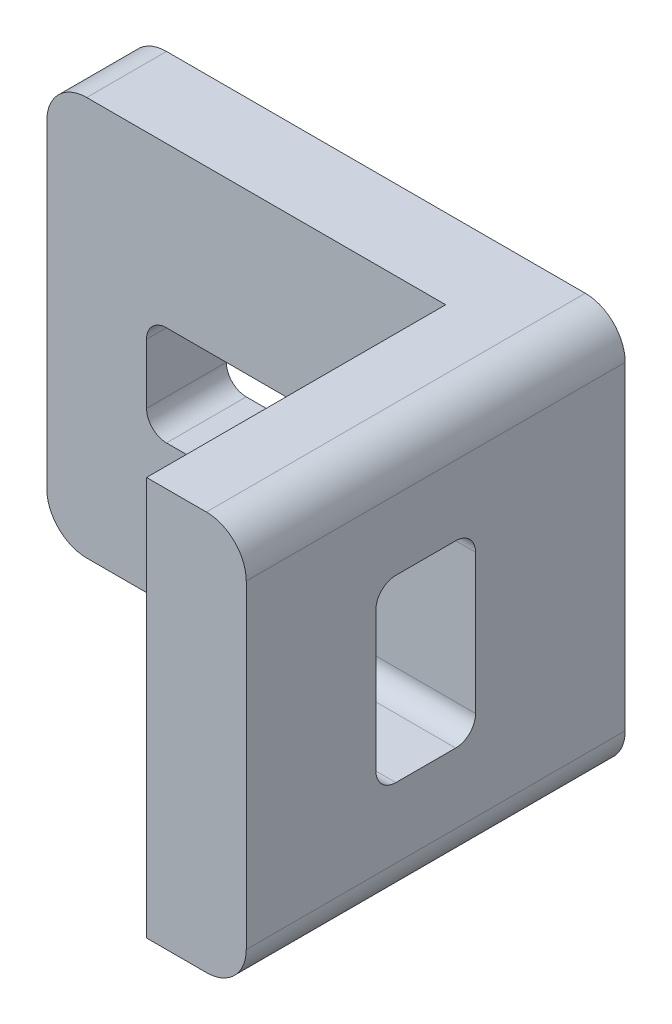
SolidWorks part; units mm, degrees
ref_plane "Plan de face" through (0, 0, 0) normal (0, 0, 1) x (1, 0, 0)
ref_plane "Plan de dessus" through (0, 0, 0) normal (0, 1, 0) x (1, 0, 0)
ref_plane "Plan de droite" through (0, 0, 0) normal (1, 0, 0) x (0, 0, -1)
sketch "Esquisse1" plane through (0, 0, 0) normal (0, 0, 1) x (1, 0, 0)
  line L1 (-11.2733, 8.7087) -> (9.7267, 8.7087)
  line L2 (-13.2733, 6.7087) -> (-13.2733, -9.2913)
  line L3 (-11.2733, -11.2913) -> (9.7267, -11.2913)
  line L4 (11.7267, 6.7087) -> (11.7267, -9.2913)
  arc A0 (9.7267, 8.7087) -> (11.7267, 6.7087) centre (9.7267, 6.7087) cw
  arc A1 (11.7267, -9.2913) -> (9.7267, -11.2913) centre (9.7267, -9.2913) cw
  arc A2 (-11.2733, -11.2913) -> (-13.2733, -9.2913) centre (-11.2733, -9.2913) cw
  arc A3 (-13.2733, 6.7087) -> (-11.2733, 8.7087) centre (-11.2733, 6.7087) cw
  point P8 (11.7267, -11.2913)
  point P11 (-13.2733, -11.2913)
  point P14 (-13.2733, 8.7087)
  dimension "D3" = 2
  dimension "D1" = 20
  dimension "D2" = 25
extrude "Boss.-Extru.1" add sketch "Esquisse1" along normal blind 4
sketch "Esquisse2" plane through (0, 0, 4) normal (0, 0, 1) x (1, 0, 0)
  line L1 (6.7267, 8.7087) -> (9.7267, 8.7087)
  line L2 (6.7267, 8.7087) -> (6.7267, -11.2913)
  line L3 (6.7267, -11.2913) -> (9.7267, -11.2913)
  line L4 (11.7267, 6.7087) -> (11.7267, -9.2913)
  line L5 (11.7267, -9.2913) -> (11.7267, 6.7087) construction
  line L6 (9.7267, 8.7087) -> (-11.2733, 8.7087) construction
  line L7 (-11.2733, -11.2913) -> (9.7267, -11.2913) construction
  arc A0 (9.7267, 8.7087) -> (11.7267, 6.7087) centre (9.7267, 6.7087) cw
  arc A1 (11.7267, -9.2913) -> (9.7267, -11.2913) centre (9.7267, -9.2913) cw
  dimension "D1" = 2
  dimension "D2" = 3
extrude "Boss.-Extru.3" add sketch "Esquisse2" along normal blind 15
sketch "Esquisse3" plane through (0, 0, 4) normal (0, 0, 1) x (1, 0, 0)
  line L0 (-13.2733, 6.7087) -> (-13.2733, -9.2913) construction
  line L1 (-7.2733, 0.7087) -> (-0.2733, 0.7087)
  line L2 (-8.2733, -0.2913) -> (-8.2733, -3.2913)
  line L3 (-7.2733, -4.2913) -> (-0.2733, -4.2913)
  line L4 (0.7267, -0.2913) -> (0.7267, -3.2913)
  line L5 (-8.2733, 0.7087) -> (0.7267, -4.2913) construction
  line L6 (-8.2733, -4.2913) -> (0.7267, 0.7087) construction
  line L7 (-11.2733, -11.2913) -> (6.7267, -11.2913) construction
  line L8 (6.7267, 8.7087) -> (-11.2733, 8.7087) construction
  arc A0 (-8.2733, -0.2913) -> (-7.2733, 0.7087) centre (-7.2733, -0.2913) cw
  arc A1 (-8.2733, -3.2913) -> (-7.2733, -4.2913) centre (-7.2733, -3.2913) ccw
  arc A2 (-0.2733, -4.2913) -> (0.7267, -3.2913) centre (-0.2733, -3.2913) ccw
  arc A3 (0.7267, -0.2913) -> (-0.2733, 0.7087) centre (-0.2733, -0.2913) ccw
  point P0 (-3.7733, -1.7913)
  dimension "D4" = 1
  dimension "D1" = 9
  dimension "D2" = 5
  dimension "D3" = 5
  dimension "D5" = 7
  dimension "D6" = 8
extrude "Enlèv. mat.-Extru.1" cut sketch "Esquisse3" against normal blind 50
sketch "Esquisse4" plane through (6.7267, 0, 0) normal (-1, 0, 0) x (0, 0, 1)
  line L0 (8.5, 3.2087) -> (11.5, 3.2087)
  line L1 (7.5, 2.2087) -> (7.5, -4.7913)
  line L2 (8.5, -5.7913) -> (11.5, -5.7913)
  line L3 (12.5, 2.2087) -> (12.5, -4.7913)
  line L4 (19, 8.7087) -> (4, 8.7087) construction
  line L7 (4, 8.7087) -> (4, -11.2913) construction
  arc A0 (7.5, 2.2087) -> (8.5, 3.2087) centre (8.5, 2.2087) cw
  arc A1 (7.5, -4.7913) -> (8.5, -5.7913) centre (8.5, -4.7913) ccw
  arc A2 (11.5, -5.7913) -> (12.5, -4.7913) centre (11.5, -4.7913) ccw
  arc A3 (12.5, 2.2087) -> (11.5, 3.2087) centre (11.5, 2.2087) ccw
  dimension "D1" = 5
  dimension "D2" = 5.5
  dimension "D3" = 9
  dimension "D4" = 3.5
extrude "Enlèv. mat.-Extru.2" cut sketch "Esquisse4" against normal blind 50
